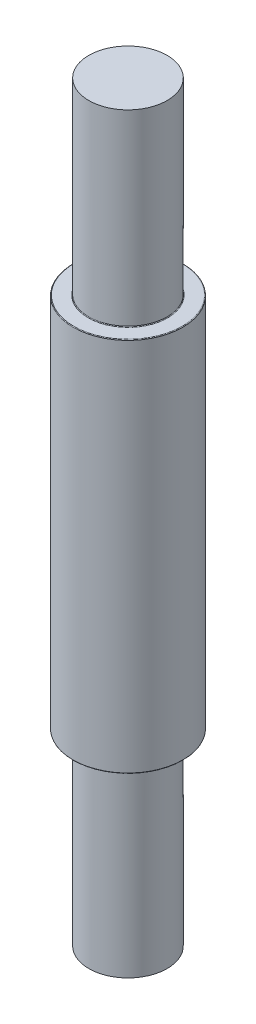
SolidWorks part; units mm, degrees
ref_plane "Front Plane" through (0, 0, 0) normal (0, 0, 1) x (1, 0, 0)
ref_plane "Top Plane" through (0, 0, 0) normal (0, 1, 0) x (1, 0, 0)
ref_plane "Right Plane" through (0, 0, 0) normal (1, 0, 0) x (0, 0, -1)
sketch "Sketch1" plane through (0, 0, 0) normal (0, 1, 0) x (1, 0, 0)
  circle A0 centre (0, 0) radius 15.875
  dimension "D1" = 31.75
extrude "Boss-Extrude1" add sketch "Sketch1" along normal blind 76.2 contours A0
sketch "Sketch2" plane through (0, 76.2, 0) normal (0, 1, 0) x (1, 0, 0)
  circle A0 centre (0, 0) radius 22.225
  dimension "D1" = 44.45
extrude "Boss-Extrude2" add sketch "Sketch2" along normal blind 152.4
sketch "Sketch3" plane through (0, 228.6, 0) normal (0, 1, 0) x (1, 0, 0)
  circle A0 centre (0, 0) radius 15.875
  dimension "D1" = 31.75
extrude "Boss-Extrude3" add sketch "Sketch3" along normal blind 76.2
fillet "Fillet1" radius 0.254 1 edges at (0, 76.2, 15.875)
fillet "Fillet2" radius 0.254 1 edges at (0, 228.6, 15.875)
fillet "Fillet3" radius 0.254 1 edges at (0, 228.6, 22.225)
fillet "Fillet4" radius 0.254 1 edges at (0, 76.2, 22.225)
